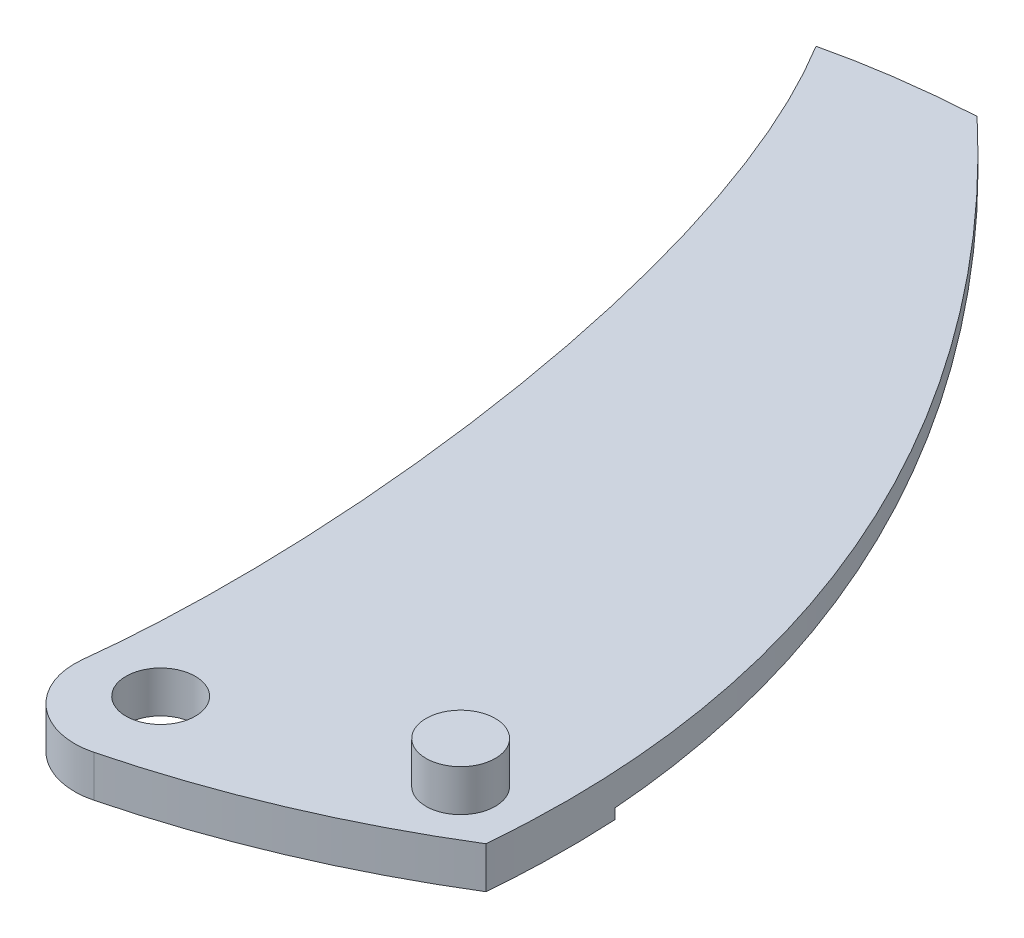
SolidWorks part; units mm, degrees
ref_plane "前视基准面" through (0, 0, 0) normal (0, 0, 1) x (1, 0, 0)
ref_plane "上视基准面" through (0, 0, 0) normal (0, 1, 0) x (1, 0, 0)
ref_plane "右视基准面" through (0, 0, 0) normal (1, 0, 0) x (0, 0, -1)
sketch "草图1" plane through (0, 0, 0) normal (0, 1, 0) x (1, 0, 0)
  circle A0 centre (0, 0) radius 72.5
  spline S0 degree 3 poles (0, 0) (14.7026, 17.1919) (49.7472, 31.7537) (64.9531, 32.2078) knots 0 0 0 0 1 1 1 1
  spline S1 degree 3 poles (0, 0) (21.9998, 5.2666) (58.9107, -3.5514) (71.4795, -12.1218) knots 0 0 0 0 1 1 1 1
  spline S4 degree 3 poles (0, 0) (20.8938, -8.6704) (45.5723, -37.5) (50.7031, -51.8213) knots 0 0 0 0 1 1 1 1
  spline S7 degree 3 poles (0, 0) (11.8071, -19.2956) (14.8268, -57.1249) (10.5599, -71.7268) knots 0 0 0 0 1 1 1 1
  spline S8 degree 3 poles (0, 0) (-1.7895, -22.5505) (-21.582, -54.93) (-33.6169, -64.2352) knots 0 0 0 0 1 1 1 1
  spline S9 degree 3 poles (0, 0) (-14.7026, -17.1919) (-49.7472, -31.7537) (-64.9531, -32.2078) knots 0 0 0 0 1 1 1 1
  spline S10 degree 3 poles (0, 0) (-21.9998, -5.2666) (-58.9107, 3.5514) (-71.4795, 12.1218) knots 0 0 0 0 1 1 1 1
  spline S11 degree 3 poles (0, 0) (-20.8938, 8.6704) (-45.5723, 37.5) (-50.7031, 51.8213) knots 0 0 0 0 1 1 1 1
  spline S12 degree 3 poles (0, 0) (-11.8071, 19.2956) (-14.8268, 57.1249) (-10.5599, 71.7268) knots 0 0 0 0 1 1 1 1
  spline S13 degree 3 poles (0, 0) (1.7895, 22.5505) (21.582, 54.93) (33.6169, 64.2352) knots 0 0 0 0 1 1 1 1
  point P15 (0, 0)
  point P16 (0, 0)
  dimension "D1" = 145
sketch "草图5" plane through (0, 0, 0) normal (0, 1, 0) x (1, 0, 0)
  circle A6 centre (0, 0) radius 72.5 construction
  arc A7 (10.5599, -71.7268) -> (71.4795, -12.1218) centre (0, 0) ccw
  spline S1 degree 3 poles (-605.4125, -2930.8983) (259.348, 3350.9419) (59.2598, -3435.4219) (-264.0358, 2913.2028) knots -3.825817 -3.825817 -3.825817 -3.825817 4.735245 4.735245 4.735245 4.735245 only from (0, 0) to (10.5599, -71.7268) construction
  spline S3 degree 3 poles (0, 0) (11.8071, -19.2956) (14.8268, -57.1249) (10.5599, -71.7268) knots 0 0 0 0 1 1 1 1
  spline S6 degree 3 poles (2600.3672, -1481.4789) (-3106.7922, 1282.1526) (3285.5926, -1005.2444) (-2852.212, 649.1162) knots -3.825817 -3.825817 -3.825817 -3.825817 4.735245 4.735245 4.735245 4.735245 only from (0, 0) to (71.4795, -12.1218) construction
  spline S7 degree 3 poles (0, 0) (21.9998, 5.2666) (58.9107, -3.5514) (71.4795, -12.1218) knots 0 0 0 0 1 1 1 1
extrude "凸台-拉伸2" add sketch "草图5" along normal blind 3
sketch "草图6" plane through (0, 0, 0) normal (0, 1, 0) x (1, 0, 0)
  line L0 (10.1932, 1.4345) -> (79.7339, 38.033)
  line L1 (79.7339, 38.033) -> (67.6196, -86.2984)
  line L2 (67.6196, -86.2984) -> (37.9434, -61.7782)
  circle A0 centre (16.9804, -64.2955) radius 2.5
  arc A1 (10.5599, -71.7268) -> (71.4795, -12.1218) centre (0, 0) ccw construction
  spline S0 degree 3 poles (10.1932, 1.4345) (25.4705, -12.9854) (40.3135, -34.9779) (37.9434, -61.7782) knots 0 0 0 0 1 1 1 1
  spline S4 degree 3 poles (0, 0) (21.9998, 5.2666) (58.9107, -3.5514) (71.4795, -12.1218) knots 0 0 0 0 1 1 1 1 construction
  spline S5 degree 3 poles (71.4795, -12.1218) (58.9107, -3.5514) (21.9998, 5.2666) (0, 0) knots 0 0 0 0 1 1 1 1 construction
  dimension "D1" = 66.5
  dimension "D2" = 5
extrude "切除-拉伸3" cut sketch "草图6" along normal blind 3
fillet "圆角1" radius 5 1 edges at (10.5599, 1.5, 71.7268)
sketch "草图9" plane through (0, 0, 0) normal (0, 1, 0) x (1, 0, 0)
  line L0 (37.78, -48.8639) -> (25.204, -53.2598)
  spline S1 degree 3 poles (10.1932, 1.4345) (25.4705, -12.9854) (40.3135, -34.9779) (37.9434, -61.7782) knots 0 0 0 0 1 1 1 1 construction
sketch "草图12" plane through (0, 0, 0) normal (0, 1, 0) x (1, 0, 0)
  circle A0 centre (33.4475, -59.1028) radius 2.5
extrude "凸台-拉伸3" add sketch "草图12" along normal blind 3 from offset 3
sketch "草图14" plane through (0, 0, 0) normal (0, 1, 0) x (1, 0, 0)
  line L0 (16.9804, -64.2955) -> (33.4475, -59.1028)
  line L1 (27.726, -69.6655) -> (20.3078, -46.1411)
ref_plane "基准面1" through (20.3078, 0, 46.1411) normal (0.9537, 0, -0.3007) x (-0.3007, 0, -0.9537)
sketch "草图15" plane through (20.3078, 0, 46.1411) normal (0.9537, 0, -0.3007) x (-0.3007, 0, -0.9537)
  line L0 (-11.5106, 0.7346) -> (50.1124, 2.1408)
  line L1 (50.1124, 3) -> (50.1124, 0) construction
  line L2 (50.1124, 2.1408) -> (51.6732, 2.1408)
  line L3 (51.6732, 2.1408) -> (51.6732, -11.4013)
  line L4 (51.6732, -11.4013) -> (-11.5106, -3.9818)
  line L5 (-11.5106, -3.9818) -> (-11.5106, 0.7346)
extrude "切除-拉伸4" cut sketch "草图15" against normal through all both and the other way through all
